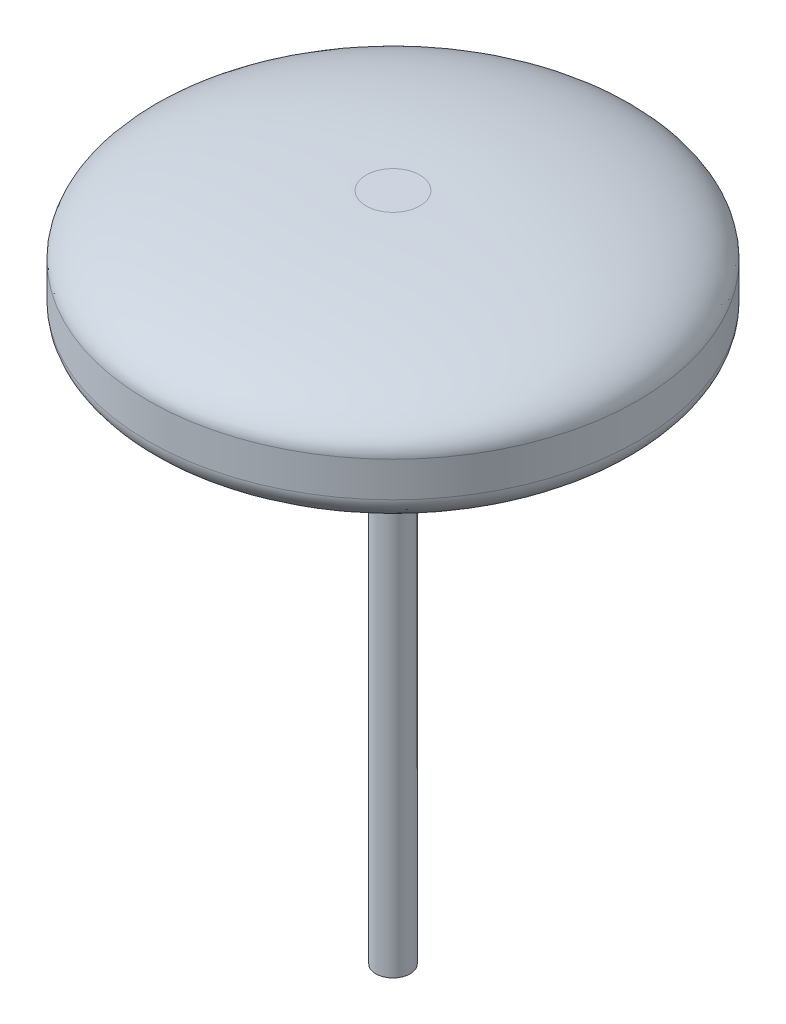
SolidWorks part; units mm, degrees
ref_plane "Front Plane" through (0, 0, 0) normal (0, 0, 1) x (1, 0, 0)
ref_plane "Top Plane" through (0, 0, 0) normal (0, 1, 0) x (1, 0, 0)
ref_plane "Right Plane" through (0, 0, 0) normal (1, 0, 0) x (0, 0, -1)
sketch "Sketch7" plane through (0, 0, 0) normal (0, 0, 1) x (1, 0, 0)
  line L0 (28.5, -2.0442) -> (28.5, 2.0442)
  line L1 (3.1211, 9) -> (0, 9)
  line L2 (0, 0) -> (30.056, 0) construction
  line L3 (0, 0) -> (0, 13.8517) construction
  line L4 (3.1211, -9) -> (0, -9)
  line L5 (0, 9) -> (0, -9)
  spline S0 degree 3 poles (28.5, 2.0442) (28.5, 5.9801) (17.4527, 9) (3.1211, 9) knots 0 0 0 0 1 1 1 1
  spline S1 degree 3 poles (28.5, -2.0442) (28.5, -5.9801) (17.4527, -9) (3.1211, -9) knots 0 0 0 0 1 1 1 1
  point P11 (28.5, 0)
  dimension "D1" = 28.5
  dimension "D2" = 9
revolve "Revolve2" add sketch "Sketch7" angle 360 about L3
sketch "Sketch8" plane through (0, -9, 0) normal (0, -1, 0) x (1, 0, 0)
  circle A0 centre (0, 0) radius 2
  dimension "D1" = 4
extrude "Boss-Extrude3" add sketch "Sketch8" along normal blind 60
